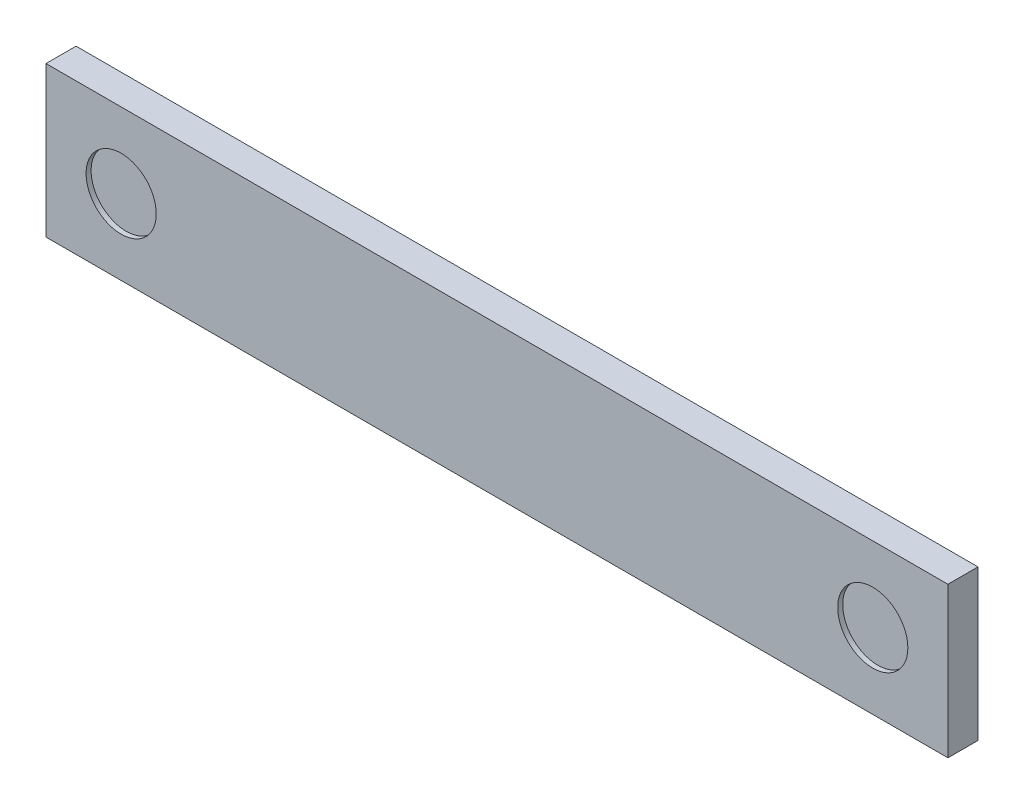
SolidWorks part; units mm, degrees
ref_plane "Plan de face" through (0, 0, 0) normal (0, 0, 1) x (1, 0, 0)
ref_plane "Plan de dessus" through (0, 0, 0) normal (0, 1, 0) x (1, 0, 0)
ref_plane "Plan de droite" through (0, 0, 0) normal (1, 0, 0) x (0, 0, -1)
sketch "Esquisse1" plane through (0, 0, 0) normal (0, 0, 1) x (1, 0, 0)
  line L1 (0, 0) -> (-1800, 0)
  line L2 (0, 0) -> (0, 300)
  line L3 (0, 300) -> (-1800, 300)
  line L4 (-1800, 0) -> (-1800, 300)
  dimension "D1" = 1800
  dimension "D2" = 300
extrude "Boss.-Extru.1" add sketch "Esquisse1" along normal blind 60
sketch "Esquisse2" plane through (0, 0, 60) normal (0, 0, 1) x (1, 0, 0)
  line L0 (0, 300) -> (-1800, 300) construction
  line L1 (0, 0) -> (0, 300) construction
  line L2 (-1800, 0) -> (0, 0) construction
  line L3 (-1800, 300) -> (-1800, 0) construction
  circle A0 centre (-150, 150) radius 70
  circle A1 centre (-1650, 150) radius 70
  point P12 (-1782.0168, 163.6898)
  dimension "D3" = 140
  dimension "D4" = 140
  dimension "D5" = 150
  dimension "D1" = 150
  dimension "D2" = 150
  dimension "D6" = 150
extrude "Enlèv. mat.-Extru.1" cut sketch "Esquisse2" against normal blind 10
